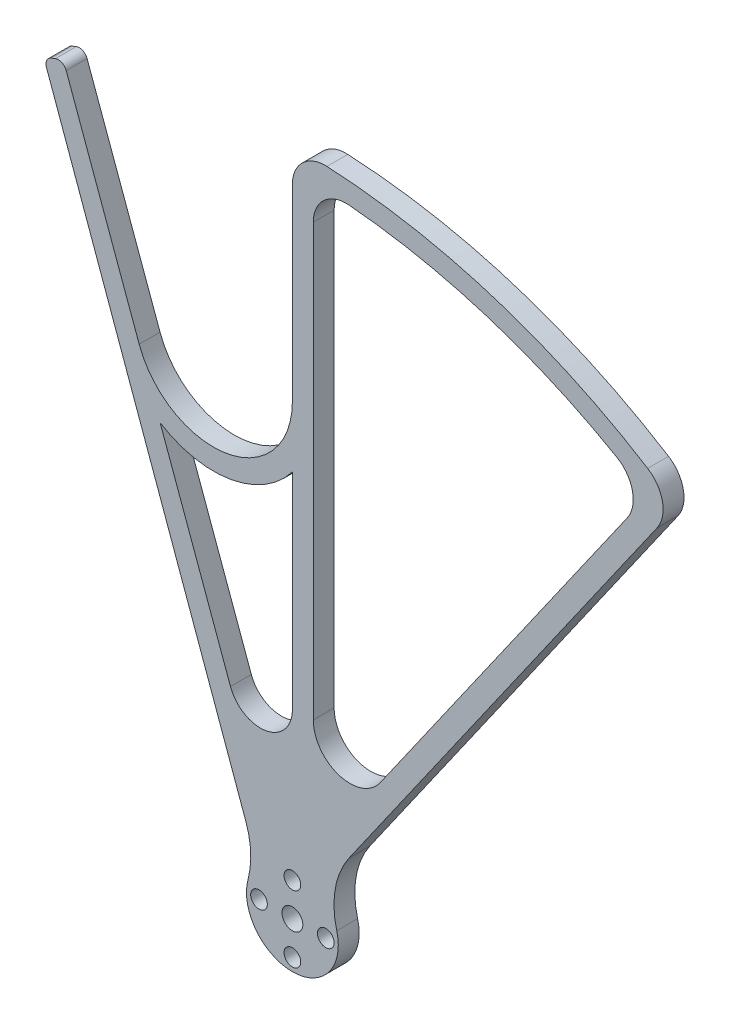
SolidWorks part; units mm, degrees
ref_plane "Front Plane" through (0, 0, 0) normal (0, 0, 1) x (1, 0, 0)
ref_plane "Top Plane" through (0, 0, 0) normal (0, 1, 0) x (1, 0, 0)
ref_plane "Right Plane" through (0, 0, 0) normal (1, 0, 0) x (0, 0, -1)
sketch "Sketch1" plane through (0, 0, 0) normal (0, 0, 1) x (1, 0, 0)
  line L2 (-75.6715, 189.251) -> (-10.703, 8.9782)
  line L3 (-69.7101, 191.527) -> (-75.6772, 189.3552)
  line L7 (26.6808, 49.1751) -> (108.0033, 165.3155)
  line L8 (6.35, 55.5854) -> (6.35, 197.3667)
  line L9 (-46.6279, 128.1092) -> (-69.7101, 191.527)
  line L10 (-1.1027, 6.2535) -> (-31.1104, 176.4361) construction
  line L11 (0, 55.1024) -> (0, 117.7403)
  line L12 (0, 0) -> (0, 203.8188) construction
  line L13 (8.0129, 11.4436) -> (116.9057, 166.9586)
  line L14 (0, 0) -> (116.9057, 166.9586) construction
  line L15 (-40.2695, 110.6396) -> (-18.8461, 51.7794)
  line L16 (0, 136.331) -> (0, 203.8188)
  line L17 (6.35, 20.1396) -> (108.0033, 165.3155) construction
  line L18 (6.35, 20.1396) -> (6.35, 197.3667) construction
  circle A1 centre (-31.1104, 176.4361) radius 28.575
  arc A3 (-69.7101, 191.527) -> (-75.6715, 189.251) centre (0, 0) ccw
  arc A4 (116.9057, 166.9586) -> (0, 203.8188) centre (0, 0) ccw
  arc A5 (108.0033, 165.3155) -> (6.35, 197.3667) centre (0, 0) ccw
  circle A6 centre (0, 0) radius 3.175
  arc A8 (-46.6279, 128.1092) -> (0, 136.331) centre (-24.0388, 136.331) ccw
  arc A10 (-40.2695, 110.6396) -> (0, 117.7403) centre (-24.0388, 136.331) ccw
  arc A11 (-18.8461, 51.7794) -> (0, 55.1024) centre (-9.716, 55.1024) ccw
  arc A12 (26.6808, 49.1751) -> (6.35, 55.5854) centre (17.526, 55.5854) cw
  arc A13 (-10.703, 8.9782) -> (8.0129, 11.4436) centre (0, 0) ccw
  dimension "D1" = 57.15
  dimension "D6" = 6.35
  dimension "D2" = 197.4688
  dimension "D7" = 20
  dimension "D10" = 11.176
  dimension "D8" = 27.94
  dimension "D3" = 6.35
  dimension "D5" = 6.35
  dimension "D9" = 35
extrude "Base Extrude" add sketch "Sketch1" along normal blind 6.35
fillet "Fillet1" radius 10 4 edges at (116.9057, 166.9586, 3.175) (0, 203.8188, 3.175) (108.0033, 165.3155, 3.175) (6.35, 197.3667, 3.175)
fillet "Fillet2" radius 2.54 2 edges at (-69.7101, 191.527, 3.175) (-75.6715, 189.251, 3.175)
sketch "Sketch2" plane through (0, 0, 6.35) normal (0, 0, 1) x (1, 0, 0)
  circle A1 centre (0, 10.16) radius 2.54
  circle A2 centre (10.16, 0) radius 2.54
  circle A3 centre (0, -10.16) radius 2.54
  circle A4 centre (-10.16, 0) radius 2.54
  point P12 (0, 0)
  dimension "D2" = 5.08
  dimension "D1" = 10.16
  dimension "D3" = 4
extrude "Mount Holes" cut sketch "Sketch2" against normal through all
fillet "Fillet3" radius 25.24 2 edges at (8.0129, 11.4436, 3.175) (-10.703, 8.9782, 3.175)
